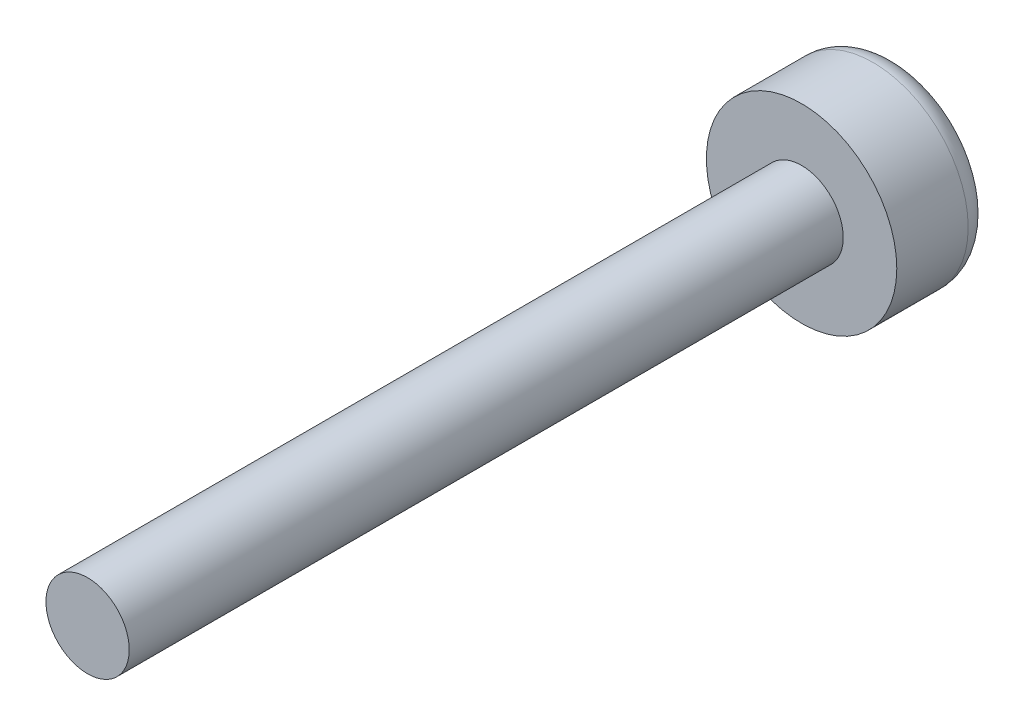
SolidWorks part; units mm, degrees
ref_plane "Alzado" through (0, 0, 0) normal (0, 0, 1) x (1, 0, 0)
ref_plane "Planta" through (0, 0, 0) normal (0, 1, 0) x (1, 0, 0)
ref_plane "Vista lateral" through (0, 0, 0) normal (1, 0, 0) x (0, 0, -1)
sketch "Croquis1" plane through (0, 0, 0) normal (0, 0, 1) x (1, 0, 0)
  circle A0 centre (0, 0) radius 4
  dimension "D1" = 8
extrude "Saliente-Extruir1" add sketch "Croquis1" along normal blind 4
sketch "Croquis2" plane through (0, 0, 4) normal (0, 0, 1) x (1, 0, 0)
  circle A0 centre (0, 0) radius 1.75
  dimension "D1" = 3.5
extrude "Saliente-Extruir2" add sketch "Croquis2" along normal blind 30
fillet "Redondeo2" radius 1 1 edges at (4, 0, 0)
